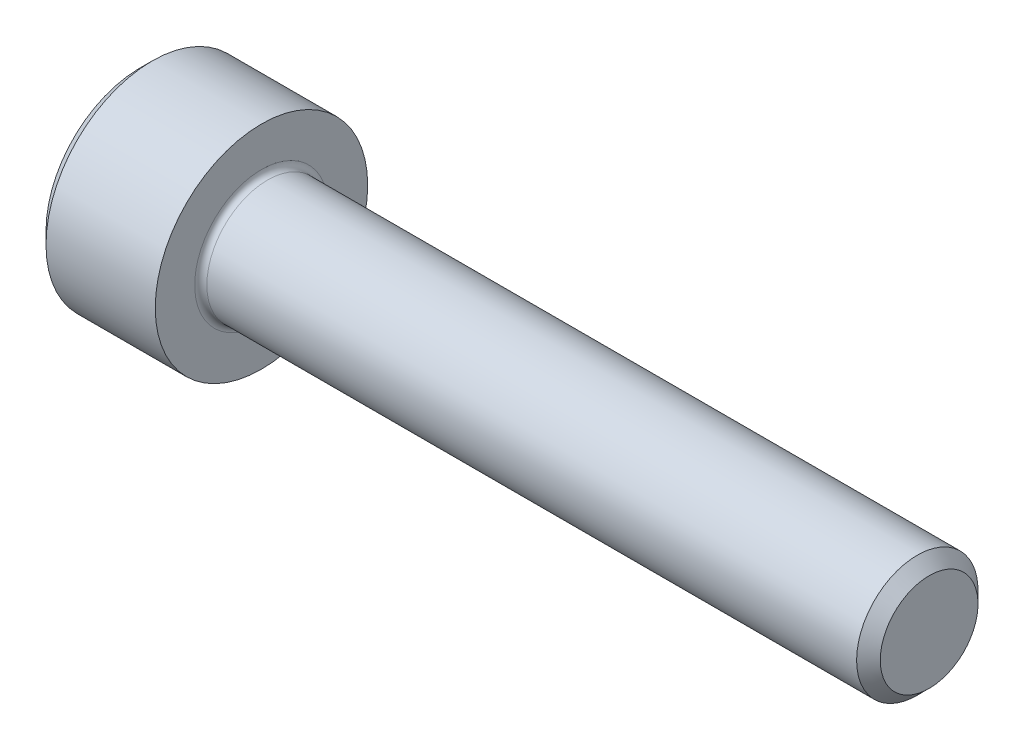
SolidWorks part; units mm, degrees
revolve "Base-Revolve" add sketch "BodySke"
sketch "BodySke" plane through (0, 0, 0) normal (0, 0, 1) x (1, 0, 0)
  line L0 (0, 0) -> (0, 3.1)
  line L1 (0.4, 3.5) -> (4, 3.5)
  line L2 (4, 3.5) -> (4, 2)
  line L3 (4, 2) -> (25.61, 2)
  line L4 (26, 1.61) -> (26, 0)
  line L5 (26, 0) -> (0, 0)
  line L6 (-31.75, 0) -> (127, 0) construction
  line L7 (0, 3.1) -> (0.4, 3.5)
  line L8 (26, 1.61) -> (25.61, 2)
  line L9 (0, -3.1) -> (0.4, -3.5) construction
  line L10 (26, -1.61) -> (25.61, -2) construction
  line L11 (4.7, 9.525) -> (4.7, 3.175) construction
  line L12 (8, 9.525) -> (8, 3.175) construction
  line L13 (-24, 9.525) -> (-24, 3.175) construction
  dimension "Diameter" = 4
  dimension "Head_ht" = 4
  dimension "Length" = 22
  dimension "Body_ch_ang" = 45
  dimension "Head_dia" = 7
  dimension "Head_ch_ang" = 45
  dimension "Minor_dia" = 3.22
  dimension "Advance" = 0.7
  dimension "Thread_nom" = 18
  dimension "Thread_length" = 50
  dimension "Head_ch_ht" = 0.4
cosmetic thread "ThreadCosmetic"
fillet "Fillet1" radius 0.2 1 edges at (4, 0, 2)
ref_plane "Plane1" through (0, 0, 0) normal (0, 0, 1) x (1, 0, 0)
ref_plane "Plane2" through (0, 0, 0) normal (0, 1, 0) x (1, 0, 0)
ref_plane "Plane3" through (0, 0, 0) normal (1, 0, 0) x (0, 0, -1)
sketch "Sketch2" plane through (0, 0, 0) normal (0, 0, 1) x (1, 0, 0)
  line L0 (0, 1.5355) -> (2, 1.5355)
  line L1 (2, 1.5355) -> (2.8865, 0)
  line L2 (-31.75, 0) -> (127, 0) construction
  line L3 (2.8865, 0) -> (0, 0)
  line L4 (0, 0) -> (0, 1.5355)
  line L5 (0, 3.1) -> (0, -3.1) construction
  line L6 (0, 0) -> (47.625, 0) construction
  line L7 (4, -3.5) -> (4, 3.5) construction
  dimension "D1" = 1.5355
  dimension "D2" = 60
revolve "Hex-PreBroach" cut sketch "Sketch2" angle 360 about L6
sketch "Sketch3" plane through (0, 0, 0) normal (-1, 0, 0) x (0, 0.5, 0.866)
  line L0 (0.8865, 1.5355) -> (-0.8865, 1.5355)
  line L1 (-0.8865, 1.5355) -> (-1.773, 0)
  line L2 (0.8865, 1.5355) -> (1.773, 0)
  line L3 (0.8865, -1.5355) -> (1.773, 0)
  line L4 (0.8865, -1.5355) -> (-0.8865, -1.5355)
  line L5 (-0.8865, -1.5355) -> (-1.773, 0)
  dimension "D1" = 1.5355
  dimension "D2" = 1.5355
  dimension "Hex_size" = 3.071
extrude "Hex" cut sketch "Sketch3" against normal blind 2
sketch "Sketch4" plane through (0, 0, 0) normal (-1, 0, 0) x (0, 0, 1)
  line L0 (0, 0) -> (1.7399, 0)
  line L1 (0, 0) -> (6.1484, 3.5498) construction
  line L2 (0, 0) -> (0.8699, 1.5068)
  line L3 (1.4457, 0.3947) -> (1.6607, 0.5189)
  line L4 (1.0647, 1.0546) -> (1.2797, 1.1788)
  arc A0 (1.4457, 0.3947) -> (1.0647, 1.0546) centre (0, 0) ccw
  arc A1 (1.7399, 0) -> (1.6607, 0.5189) centre (0, 0) ccw
  arc A2 (0.8699, 1.5068) -> (1.2797, 1.1788) centre (0, 0) cw
  dimension "D1" = 30
  dimension "D2" = 60
  dimension "Spline_p_dim" = 0.762
  dimension "D3" = 0.381
extrude "Spline" [suppressed] cut sketch "Sketch4" against normal blind 2
pattern_circular "CirPattern1" [suppressed] count 6 every 60
sketch "Sketch5" plane through (0, 0, 0) normal (0, 0, 1) x (1, 0, 0)
  line L0 (-31.75, 0) -> (127, 0) construction
  line L2 (0, 3.1) -> (0, -3.1) construction
  circle A0 centre (1.6, 0) radius 0.675
  dimension "Drilled_hole_dia" = 1.35
  dimension "Drilled_hole_loc" = 1.6
extrude "Hole" [suppressed] cut sketch "Sketch5" against normal through all and the other way through all
pattern_circular "Drilled-4" [suppressed] count 2 every 60
pattern_circular "Drilled-6" [suppressed] count 3 every 60
sketch "ThdSchSke" plane through (0, 0, 0) normal (0, 0, 1) x (1, 0, 0)
  line L0 (8, -1.61) -> (7.7269, -2)
  line L1 (8, -1.61) -> (8.2731, -2)
  line L2 (8.2731, -2) -> (8.2731, -2.5)
  line L3 (-3.175, 0) -> (5.1513, 0) construction
  line L5 (8.2731, -2.5) -> (7.7269, -2.5)
  line L6 (7.7269, -2.5) -> (7.7269, -2)
  line L7 (0, 3.1) -> (0, -3.1) construction
  dimension "Thread_minor" = 3.22
  dimension "Diameter" = 4
  dimension "Start" = 8
revolve "ThreadSchematic" [suppressed] cut sketch "ThdSchSke" angle 360 about L3
pattern_linear "ThdSchPat" [suppressed]
equation "\"D2@Sketch3\" = \"Hex_size@Sketch3\" / 2"
equation "\"D1@Sketch3\" = \"Hex_size@Sketch3\" / 2"
equation "\"D1@Sketch2\" = \"Hex_size@Sketch3\" / 2"
equation "\"D3@Sketch4\" = \"Spline_p_dim@Sketch4\" / 2"
equation "\"Thread_minor@ThreadCosmetic\"  =  \"Minor_dia@BodySke\""
equation "\"D2@CirPattern1\" = 360 / \"Num_teeth@CirPattern1\""
equation "\"Wall_thickness@Sketch2\" = \"Head_ht@BodySke\" - \"Key_eng@Hex\""
equation "\"Thread_length@ThreadCosmetic\" = ((sgn( (\"Length@BodySke\" - \"Advance@BodySke\" ) - \"Thread_nom@BodySke\" )-1)*( (\"Length@BodySke\" - \"Advance@BodySke\" ) - \"Thread_nom@BodySke\" ))/-2+ \"Thread_nom@BodySke\""
equation "\"Thread_minor@ThdSchSke\" = \"Minor_dia@BodySke\""
equation "\"Diameter@ThdSchSke\" = \"Diameter@BodySke\""
equation "\"Overcut@ThdSchSke\" = \"Diameter@BodySke\" * 1.25"
equation "\"Start@ThdSchSke\" = \"Head_ht@BodySke\" + \"Length@BodySke\" - \"Thread_length@ThreadCosmetic\"  '---Non-countersunk---"
equation "\"Num_threads@ThdSchPat\" = int( \"Thread_length@ThreadCosmetic\" / \"Advance@BodySke\" + 0.999 )  + 1"
equation "\"Advance@ThdSchPat\" = \"Thread_length@ThreadCosmetic\" /  (\"Num_threads@ThdSchPat\" - 1) 'relax it"
equation "\"Num_threads@ThdSchPat\" = \"Num_threads@ThdSchPat\" - sgn( \"Num_threads@ThdSchPat\" - 1) '---chamfered tips only---"
